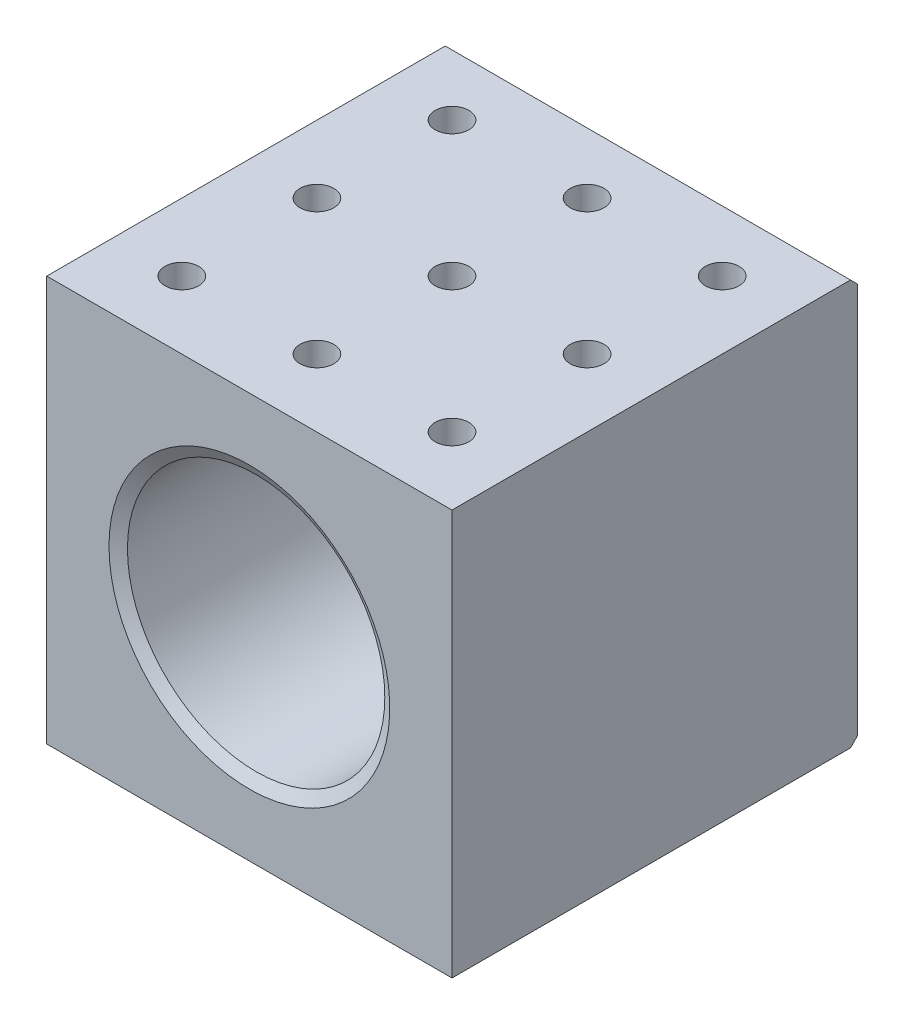
SolidWorks part; units mm, degrees
material "HDPE, Black"
ref_plane "Front Plane" through (0, 0, 0) normal (0, 0, 1) x (1, 0, 0)
ref_plane "Top Plane" through (0, 0, 0) normal (0, 1, 0) x (1, 0, 0)
ref_plane "Right Plane" through (0, 0, 0) normal (1, 0, 0) x (0, 0, -1)
sketch "Sketch1" plane through (0, 0, 0) normal (0, 0, 1) x (1, 0, 0)
  line L3 (-15, -15) -> (15, -15)
  line L4 (-15, -15) -> (-15, 15)
  line L5 (-15, 15) -> (15, 15)
  line L7 (15, 15) -> (15, -15)
  line L8 (0, 15) -> (0, -15) construction
  circle A2 centre (0, 0) radius 9.525
  point P0 (0, 0)
  point P1 (0, 0)
  dimension "D2" = 19.05
  dimension "D1" = 30
extrude "Boss-Extrude1" add sketch "Sketch1" along normal mid plane 30
chamfer "Chamfer2" distance 0.5 angle 60 2 edges at (9.525, 0, -15) (9.525, 0, 15)
chamfer "Chamfer3" distance 0.5 angle 45 2 edges at (0, -15, -15) (0, 15, -15)
mirror "Mirror1" [suppressed]
sketch "Sketch6" plane through (0, 15, 0) normal (0, 1, 0) x (1, 0, 0)
  line L0 (-10, 0) -> (10, 0) construction
  line L2 (-10, -10) -> (10, -10)
  line L3 (-10, -10) -> (-10, 10)
  line L4 (-10, 10) -> (10, 10)
  line L5 (10, -10) -> (10, 10)
  line L6 (-10, -10) -> (10, 10) construction
  line L7 (-10, 10) -> (10, -10) construction
  circle A0 centre (-10, 0) radius 1.9365
  circle A1 centre (10, 0) radius 1.9365
  point P5 (0, 0)
  dimension "D1" = 20
hole_wizard "M3x0.5 Tapped Hole1" positions "Sketch7" profile "Sketch8" tap size "M3x0.5" standard "ANSI Metric"
sketch "Sketch7" plane through (0, 15, 0) normal (0, 1, 0) x (1, 0, 0)
  line L0 (-10, 10) -> (10, 10) construction
  line L1 (-10, -10) -> (10, -10) construction
  point P0 (-10, 0)
  point P3 (10, 0)
  point P6 (0, 0)
  point P9 (-10, 10)
  point P12 (-10, -10)
  point P15 (10, 10)
  point P18 (10, -10)
  point P23 (0, 10)
  point P25 (0, -10)
sketch "Sketch8" plane through (-10, 15, 0) normal (1, 0, 0) x (0, 0, 1)
  line L0 (0, 0) -> (0, 6.7511)
  line L1 (0, 6.7511) -> (1.25, 6)
  line L2 (1.25, 6) -> (1.25, 0)
  line L5 (1.25, 0) -> (0, 0)
  line L10 (0, 6.7511) -> (-1.25, 6) construction
  line L11 (0, -6.35) -> (0, 107.95) construction
  dimension "Tap Drill Dia." = 2.5
  dimension "Tap Drill Depth" = 6
  dimension "Drill Angle" = 118
cosmetic thread "Hole Thread3" parameters "D1"=5, "D2"=3
cosmetic thread "Hole Thread4" parameters "D1"=3.0713, "D2"=3
cosmetic thread "Hole Thread9" parameters "D1"=5, "D2"=3
cosmetic thread "Hole Thread10" parameters "D1"=5, "D2"=3
cosmetic thread "Hole Thread11" parameters "D1"=5, "D2"=3
cosmetic thread "Hole Thread12" parameters "D1"=5, "D2"=3
cosmetic thread "Hole Thread13" parameters "D1"=5, "D2"=3
cosmetic thread "Hole Thread14" parameters "D1"=5, "D2"=3
cosmetic thread "Hole Thread15" parameters "D1"=5, "D2"=3
sketch "Sketch9" [suppressed] plane through (0, 0, -14.25) normal (0, 0, -1) x (-1, 0, 0)
  line L1 (0, -12) -> (-25, -12)
  line L4 (0, 0) -> (0, -12) construction
  line L5 (88, -14) -> (-88, -14) construction
  line L6 (0, -12) -> (0, -15)
  line L7 (0, -15) -> (-80, -15)
  line L8 (-80, -15) -> (-80, -14)
  arc A2 (-80, -14) -> (-78.9832, -13.963) centre (-80, 0) ccw
  arc A3 (-25, -12) -> (-78.9832, -13.963) centre (-25, -755.25) ccw
  line M13 (-88, -13.5) -> (88, -13.5)
  dimension "D1" = 50
  dimension "D3" = 12
extrude "Cut-Extrude1" [suppressed] cut sketch "Sketch9" against normal through all contours L1 A3 A2 L6 M13 | A2 L8 L7 L6 M13
mirror "Mirror2" [suppressed]
chamfer "Chamfer4" [suppressed] distance 0.5 angle 45
sketch "Sketch10" plane through (0, 0, -15) normal (0, 0, -1) x (-1, 0, 0)
  circle A0 centre (0, 0) radius 11
  dimension "D1" = 22
extrude "Cut-Extrude2" [suppressed] cut sketch "Sketch10" against normal through all
chamfer "Chamfer5" [suppressed] distance 0.254 angle 45
sketch "Sketch11" [suppressed] plane through (0, -12, 0) normal (0, -1, 0) x (1, 0, 0)
  line L0 (12.7, 0) -> (-12.7, 0) construction
  dimension "D1" = 25.4
hole_wizard "M4x0.7 Tapped Hole1" [suppressed] positions "Sketch12" profile "Sketch14" tap size "M4x0.7" standard "ANSI Metric"
sketch "Sketch12" [suppressed] plane through (0, -14, 0) normal (0, -1, 0) x (-1, 0, 0)
  point P0 (-12.7, 0)
  point P3 (12.7, 0)
sketch "Sketch14" plane through (12.7, -14, 0) normal (1, 0, 0) x (0, 0, -1)
  line L0 (0, 0) -> (0, 11.0914)
  line L1 (0, 11.0914) -> (1.65, 10.1)
  line L2 (1.65, 10.1) -> (1.65, 0)
  line L5 (1.65, 0) -> (0, 0)
  line L10 (0, 11.0914) -> (-1.65, 10.1) construction
  line L11 (0, -6.35) -> (0, 107.95) construction
  dimension "Tap Drill Dia." = 3.3
  dimension "Tap Drill Depth" = 10.1
  dimension "Drill Angle" = 118
cosmetic thread "Hole Thread5" parameters "D1"=8, "D2"=4
cosmetic thread "Hole Thread6" parameters "D1"=8, "D2"=4
sketch "Sketch15" plane through (0, -15, 0) normal (0, -1, 0) x (1, 0, 0)
  circle A0 centre (0, 0) radius 12.7 construction
  dimension "D1" = 25.4
